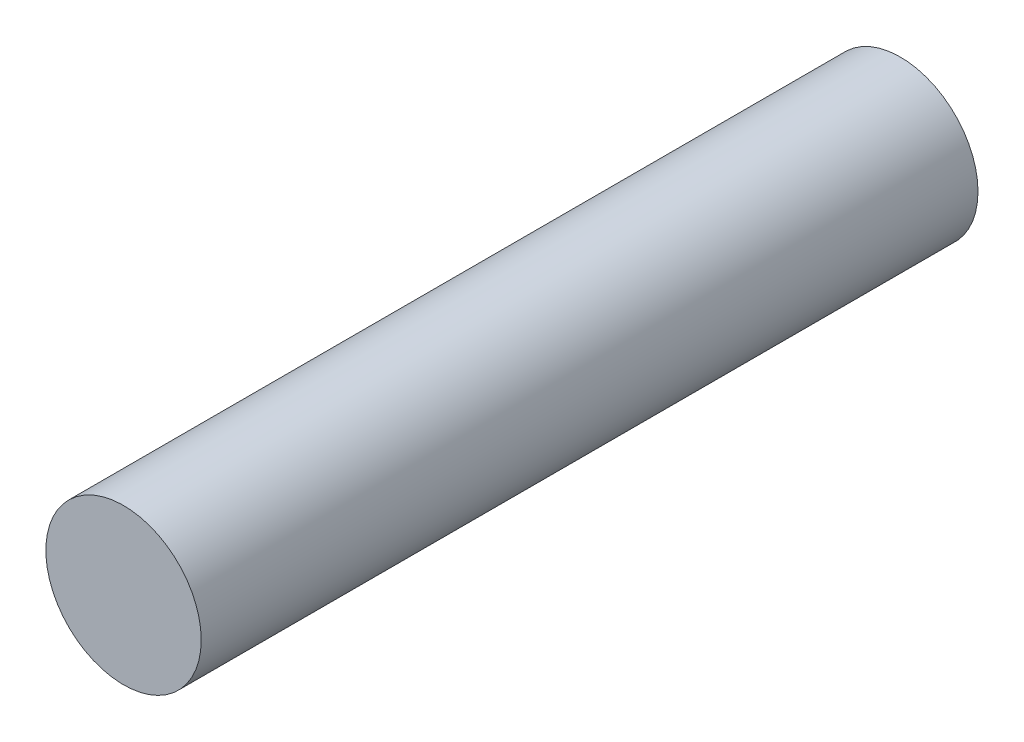
SolidWorks part; units mm, degrees
material "PET"
ref_plane "Front Plane" through (0, 0, 0) normal (0, 0, 1) x (1, 0, 0)
ref_plane "Top Plane" through (0, 0, 0) normal (0, 1, 0) x (1, 0, 0)
ref_plane "Right Plane" through (0, 0, 0) normal (1, 0, 0) x (0, 0, -1)
sketch "Sketch1" plane through (0, 0, 0) normal (0, 0, 1) x (1, 0, 0)
  circle A0 centre (0, 0) radius 3.81
  dimension "D1" = 7.62
extrude "Boss-Extrude1" add sketch "Sketch1" against normal blind 38.1
